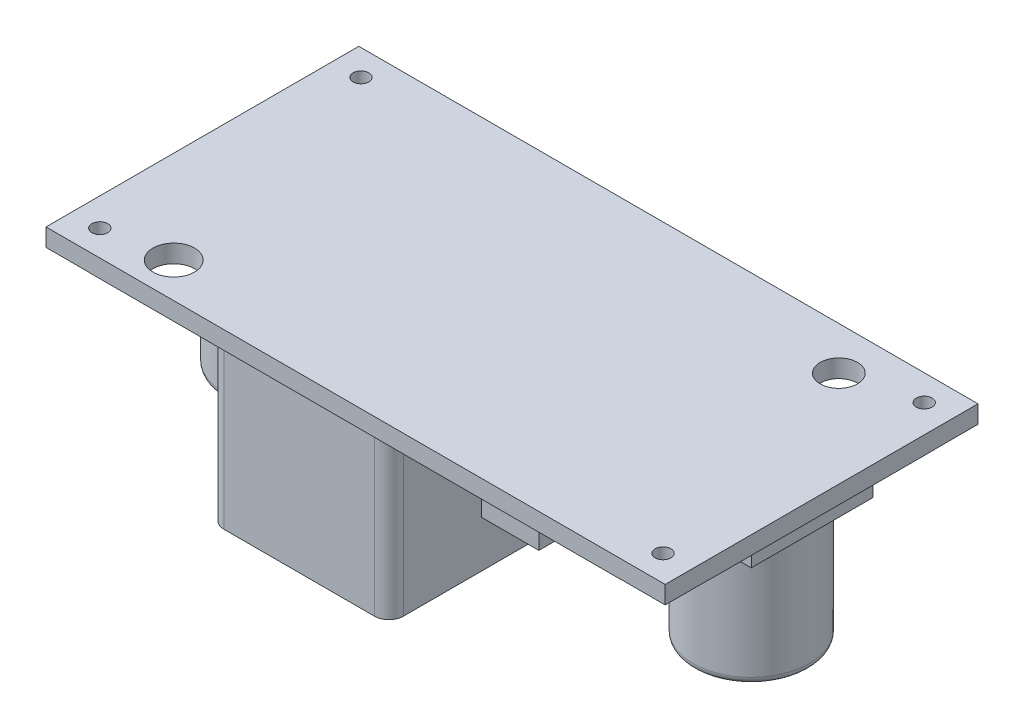
SolidWorks part; units mm, degrees
ref_plane "Front Plane" through (0, 0, 0) normal (0, 0, 1) x (1, 0, 0)
ref_plane "Top Plane" through (0, 0, 0) normal (0, 1, 0) x (1, 0, 0)
ref_plane "Right Plane" through (0, 0, 0) normal (1, 0, 0) x (0, 0, -1)
sketch "Sketch1" plane through (0, 0, 0) normal (0, 1, 0) x (1, 0, 0)
  line L1 (-21.575, -10.9) -> (21.575, -10.9)
  line L2 (-21.575, -10.9) -> (-21.575, 10.9)
  line L3 (-21.575, 10.9) -> (21.575, 10.9)
  line L4 (21.575, -10.9) -> (21.575, 10.9)
  line L5 (-21.575, -10.9) -> (21.575, 10.9) construction
  line L6 (-21.575, 10.9) -> (21.575, -10.9) construction
  point P0 (0, 0)
  dimension "D1" = 21.8
  dimension "D2" = 43.15
extrude "Boss-Extrude1" add sketch "Sketch1" along normal blind 1.25
sketch "Sketch2" plane through (0, 1.25, 0) normal (0, 1, 0) x (1, 0, 0)
  line L4 (21.575, 10.9) -> (-21.575, 10.9) construction
  line L5 (21.575, -10.9) -> (21.575, 10.9) construction
  line L6 (-21.575, -10.9) -> (21.575, -10.9) construction
  line L7 (-21.575, 10.9) -> (-21.575, -10.9) construction
  circle A0 centre (19.625, 9.1) radius 0.55
  circle A1 centre (19.625, -9.1) radius 0.55
  circle A2 centre (-19.625, 9.1) radius 0.55
  circle A3 centre (-19.625, -9.1) radius 0.55
  point P16 (20.175, 9.1)
  point P17 (19.625, 9.65)
  point P18 (-20.175, 9.1)
  point P19 (-19.625, -9.65)
  dimension "D3" = 1.1
  dimension "D1" = 1.4
  dimension "D2" = 1.25
  dimension "D4" = 1.4
  dimension "D5" = 1.25
extrude "Cut-Extrude1" cut sketch "Sketch2" against normal through all
sketch "Sketch3" plane through (0, 1.25, 0) normal (0, 1, 0) x (1, 0, 0)
  line L1 (-21.575, 10.9) -> (-21.575, -10.9) construction
  line L3 (21.575, 10.9) -> (-21.575, 10.9) construction
  line L4 (-21.575, -10.9) -> (21.575, -10.9) construction
  circle A0 centre (14.875, 7.9) radius 1.3
  circle A1 centre (-15.125, -8.45) radius 1.45
  point P4 (-16.575, -8.45)
  point P7 (16.175, 7.9)
  point P10 (14.875, 9.2)
  point P11 (-15.125, -9.9)
  dimension "D1" = 2.6
  dimension "D2" = 2.9
  dimension "D3" = 30
  dimension "D4" = 5
  dimension "D5" = 1.7
  dimension "D6" = 1
extrude "Cut-Extrude2" cut sketch "Sketch3" against normal through all
sketch "Sketch4" plane through (0, 0, 0) normal (0, -1, 0) x (1, 0, 0)
  line L1 (21.575, -10.9) -> (18.575, -10.9)
  line L2 (21.575, -10.9) -> (21.575, -7.9)
  line L3 (21.575, -7.9) -> (18.575, -7.9)
  line L4 (18.575, -10.9) -> (18.575, -7.9)
  line L5 (21.575, 10.9) -> (18.575, 10.9)
  line L6 (21.575, 10.9) -> (21.575, 7.9)
  line L7 (21.575, 7.9) -> (18.575, 7.9)
  line L8 (18.575, 10.9) -> (18.575, 7.9)
  line L9 (-21.575, 10.9) -> (-18.575, 10.9)
  line L10 (-21.575, 10.9) -> (-21.575, 7.9)
  line L11 (-21.575, 7.9) -> (-18.575, 7.9)
  line L12 (-18.575, 10.9) -> (-18.575, 7.9)
  line L13 (-21.575, -10.9) -> (-18.575, -10.9)
  line L14 (-21.575, -10.9) -> (-21.575, -7.9)
  line L15 (-21.575, -7.9) -> (-18.575, -7.9)
  line L16 (-18.575, -10.9) -> (-18.575, -7.9)
  dimension "D1" = 3
extrude "Cut-Extrude3" cut sketch "Sketch4" against normal blind 0.01
sketch "Sketch5" plane through (0, 0, 0) normal (0, -1, 0) x (1, 0, 0)
  line L0 (20.7466, -6.7043) -> (18.394, -6.7043) construction
  line L1 (20.7466, 7.55) -> (18.394, 7.55) construction
  line L2 (-17.7724, -6.7043) -> (-20.4941, -6.7043) construction
  line L3 (-17.7724, 7.55) -> (-20.4941, 7.55) construction
  text T0 "IN+" font "Century Gothic" height 1
  text T1 "IN-" font "Century Gothic" height 1
  text T2 "OUT+" font "Century Gothic" height 1
  text T3 "OUT-" font "Century Gothic" height 1
extrude "Cut-Extrude4" cut sketch "Sketch5" against normal blind 0.01
sketch "Sketch6" plane through (0, 0, 0) normal (0, -1, 0) x (1, 0, 0)
  line L0 (-18.575, 10.9) -> (18.575, 10.9) construction
  line L1 (12.075, 3.9) -> (20.575, 3.9)
  line L2 (12.075, 3.9) -> (12.075, -4.6)
  line L3 (12.075, -4.6) -> (20.575, -4.6)
  line L4 (20.575, 3.9) -> (20.575, -4.6)
  line L5 (12.075, 3.9) -> (20.575, -4.6) construction
  line L6 (12.075, -4.6) -> (20.575, 3.9) construction
  line L7 (-20.575, 3.9) -> (-12.075, 3.9)
  line L8 (-20.575, 3.9) -> (-20.575, -4.6)
  line L9 (-20.575, -4.6) -> (-12.075, -4.6)
  line L10 (-12.075, 3.9) -> (-12.075, -4.6)
  line L11 (-20.575, 3.9) -> (-12.075, -4.6) construction
  line L12 (-20.575, -4.6) -> (-12.075, 3.9) construction
  line L13 (-21.575, -7.9) -> (-21.575, 7.9) construction
  line L14 (21.575, 7.9) -> (21.575, -7.9) construction
  point P0 (16.325, -0.35)
  point P5 (-16.325, -0.35)
  dimension "D1" = 8.5
  dimension "D2" = 7
  dimension "D3" = 1
  dimension "D4" = 1
extrude "Boss-Extrude2" add sketch "Sketch6" along normal blind 1.75
sketch "Sketch7" plane through (0, -1.75, 0) normal (0, -1, 0) x (1, 0, 0)
  line L0 (20.575, 3.9) -> (12.075, 3.9) construction
  line L1 (-12.075, -4.6) -> (-12.075, 3.9) construction
  line L2 (-12.075, 3.9) -> (-20.575, 3.9) construction
  line L3 (12.075, 3.9) -> (12.075, -4.6) construction
  circle A0 centre (-16.325, -0.35) radius 4.05
  circle A1 centre (16.325, -0.35) radius 4.05
  point P6 (16.325, 3.9)
  point P9 (-12.075, -0.35)
  point P12 (-16.325, 3.9)
  point P15 (12.075, -0.35)
  dimension "D1" = 8.1
extrude "Boss-Extrude3" add sketch "Sketch7" along normal blind 8.5
fillet "Fillet1" radius 0.5 2 edges at (16.325, -10.25, -4.4) (-16.325, -10.25, -4.4)
sketch "Sketch8" plane through (0, 0, 0) normal (0, -1, 0) x (1, 0, 0)
  line L0 (-18.575, 10.9) -> (18.575, 10.9) construction
  line L1 (-11.375, 9.7) -> (1.125, 9.7)
  line L2 (-11.375, 9.7) -> (-11.375, -2.8)
  line L3 (-11.375, -2.8) -> (1.125, -2.8)
  line L4 (1.125, 9.7) -> (1.125, -2.8)
  line L5 (-21.575, -7.9) -> (-21.575, 7.9) construction
  dimension "D1" = 12.5
  dimension "D2" = 1.2
  dimension "D3" = 10.2
extrude "Boss-Extrude4" add sketch "Sketch8" along normal blind 12
fillet "Fillet2" radius 1 4 edges at (-11.375, -6, -2.8) (1.125, -6, -2.8) (1.125, -6, 9.7) (-11.375, -6, 9.7)
sketch "Sketch9" plane through (0, 0, 0) normal (0, -1, 0) x (1, 0, 0)
  line L0 (-10.225, -4.5) -> (-10.225, -5.2)
  line L1 (-10.925, -4.5) -> (-10.225, -4.5)
  line L2 (-10.925, -4.5) -> (-10.925, -9.5)
  line L3 (-10.925, -9.5) -> (-1.425, -9.5)
  line L4 (-1.425, -4.5) -> (-1.425, -9.5)
  line L5 (-10.225, -5.2) -> (-2.125, -5.2)
  line L6 (-2.125, -5.2) -> (-2.125, -4.5)
  line L7 (-2.125, -4.5) -> (-1.425, -4.5)
  line L8 (-6.175, -5.2) -> (-6.175, -9.5) construction
  line L9 (18.575, -10.9) -> (-18.575, -10.9) construction
  line L10 (-21.575, -7.9) -> (-21.575, 7.9) construction
  dimension "D1" = 9.5
  dimension "D2" = 5
  dimension "D3" = 4.3
  dimension "D4" = 1.4
  dimension "D5" = 10.65
extrude "Boss-Extrude5" add sketch "Sketch9" along normal blind 10
sketch "Sketch10" plane through (0, 0, 0) normal (0, -1, 0) x (1, 0, 0)
  line L0 (21.575, 7.9) -> (21.575, -7.9) construction
  line L1 (7.575, 9.7) -> (11.575, 9.7)
  line L2 (7.575, 9.7) -> (7.575, 7.2)
  line L3 (7.575, 7.2) -> (11.575, 7.2)
  line L4 (11.575, 9.7) -> (11.575, 7.2)
  line L5 (-18.575, 10.9) -> (18.575, 10.9) construction
  dimension "D1" = 4
  dimension "D2" = 2.5
  dimension "D3" = 10
  dimension "D4" = 1.2
extrude "Boss-Extrude6" add sketch "Sketch10" along normal blind 2.3
sketch "Sketch11" plane through (0, 0, 0) normal (0, -1, 0) x (1, 0, 0)
  line L0 (1.125, -1.8) -> (1.125, 8.7) construction
  line L1 (1.625, 0.6) -> (11.625, 0.6)
  line L2 (1.625, 0.6) -> (1.625, -7.8)
  line L3 (1.625, -7.8) -> (11.625, -7.8)
  line L4 (11.625, 0.6) -> (11.625, -7.8)
  line L5 (18.575, -10.9) -> (-18.575, -10.9) construction
  dimension "D1" = 8.4
  dimension "D2" = 10
  dimension "D3" = 0.5
  dimension "D4" = 3.1
extrude "Boss-Extrude7" add sketch "Sketch11" along normal blind 4.3
chamfer "Chamfer1" distance 2 angle 20 2 edges at (6.625, -4.3, 0.6) (6.625, -4.3, -7.8)
sketch "Sketch12" plane through (0, 0, 0) normal (0, -1, 0) x (1, 0, 0)
  line L0 (11.625, -7.8) -> (11.625, 0.6) construction
  line L1 (1.625, -7.8) -> (11.625, -7.8)
  line L2 (1.625, -7.8) -> (1.625, -9.3)
  line L3 (1.625, -9.3) -> (11.625, -9.3)
  line L4 (11.625, -7.8) -> (11.625, -9.3)
  dimension "D1" = 1.5
extrude "Boss-Extrude8" add sketch "Sketch12" along normal blind 1
sketch "Sketch13" plane through (0, 0, 0) normal (0, -1, 0) x (1, 0, 0)
  line L0 (11.625, 0.6) -> (1.625, 0.6) construction
  line L1 (2.375, 5.6) -> (3.375, 5.6)
  line L2 (2.375, 5.6) -> (2.375, 0.6)
  line L3 (2.375, 0.6) -> (3.375, 0.6)
  line L4 (3.375, 5.6) -> (3.375, 0.6)
  line L5 (1.625, -0.1279) -> (1.625, 0.6) construction
  dimension "D1" = 0.75
  dimension "D2" = 1
  dimension "D3" = 5
extrude "Boss-Extrude9" add sketch "Sketch13" along normal blind 1
pattern_linear "LPattern1" count 5 spacing 1.9 along (1, 0, 0) of "Boss-Extrude9"
sketch "Sketch14" plane through (0, -10, 0) normal (0, -1, 0) x (1, 0, 0)
  line L0 (-10.925, -9.5) -> (-1.425, -9.5) construction
  line L1 (-1.425, -9.5) -> (-1.425, -4.5) construction
  circle A0 centre (-2.575, -8.2) radius 1.15
  dimension "D1" = 2.3
  dimension "D2" = 1.3
extrude "Boss-Extrude10" add sketch "Sketch14" along normal blind 1.6
